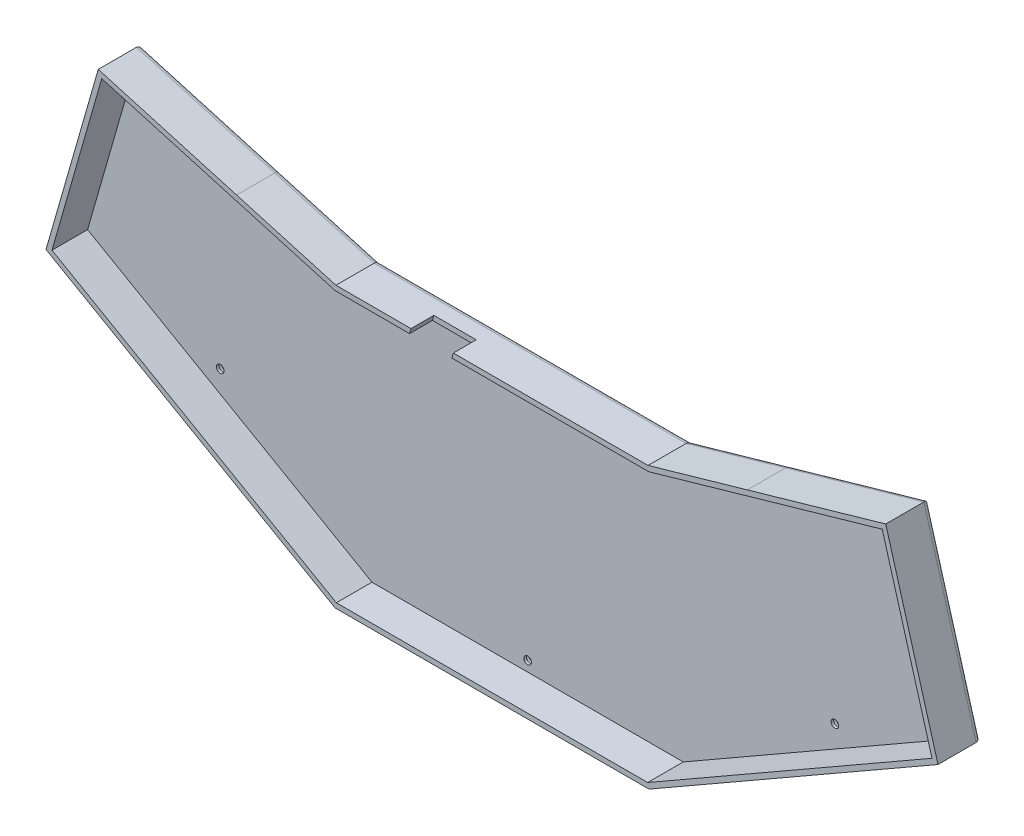
SolidWorks part; units mm, degrees
ref_plane "Plan de face" through (0, 0, 0) normal (0, 0, 1) x (1, 0, 0)
ref_plane "Plan de dessus" through (0, 0, 0) normal (0, 1, 0) x (1, 0, 0)
ref_plane "Plan de droite" through (0, 0, 0) normal (1, 0, 0) x (0, 0, -1)
sketch "Esquisse1" plane through (0, 0, 0) normal (0, 0, 1) x (1, 0, 0)
  line L0 (229.1572, -14.8472) -> (106.4333, -14.8472)
  line L1 (106.4333, -14.8472) -> (67.3725, -3.6491)
  line L2 (67.3725, -3.6491) -> (12.9612, 11.9531)
  line L3 (12.9612, 11.9531) -> (-7.5845, -59.6983)
  line L4 (-7.5845, -59.6983) -> (106.0528, -124.8987)
  line L5 (106.0528, -124.8987) -> (229.5377, -124.8987)
  line L6 (229.5377, -124.8987) -> (343.175, -59.6983)
  line L7 (343.175, -59.6983) -> (322.6293, 11.9531)
  line L8 (322.6293, 11.9531) -> (268.218, -3.6491)
  line L9 (268.218, -3.6491) -> (229.1572, -14.8472)
  line L10 (229.4382, -16.8472) -> (106.1523, -16.8472)
  line L11 (106.1523, -16.8472) -> (66.8213, -5.5716)
  line L12 (66.8213, -5.5716) -> (14.3325, 9.4793)
  line L13 (14.3325, 9.4793) -> (-5.2301, -58.7434)
  line L14 (-5.2301, -58.7434) -> (106.5858, -122.8987)
  line L15 (106.5858, -122.8987) -> (229.0047, -122.8987)
  line L16 (229.0047, -122.8987) -> (340.8206, -58.7434)
  line L17 (340.8206, -58.7434) -> (321.2581, 9.4793)
  line L18 (321.2581, 9.4793) -> (268.7692, -5.5716)
  line L19 (268.7692, -5.5716) -> (229.4382, -16.8472)
  line L20 (322.9036, 12.4479) -> (268.1078, -3.2646) construction
  line L21 (268.1078, -3.2646) -> (229.101, -14.4472) construction
  line L22 (229.101, -14.4472) -> (106.4895, -14.4472) construction
  line L23 (106.4895, -14.4472) -> (67.4828, -3.2646) construction
  line L24 (67.4828, -3.2646) -> (12.687, 12.4479) construction
  line L25 (12.687, 12.4479) -> (-8.0554, -59.8893) construction
  line L26 (-8.0554, -59.8893) -> (105.9462, -125.2987) construction
  line L27 (105.9462, -125.2987) -> (229.6443, -125.2987) construction
  line L28 (229.6443, -125.2987) -> (343.6459, -59.8893) construction
  line L29 (343.6459, -59.8893) -> (322.9036, 12.4479) construction
  line L56 (242.979, -13.5895) -> (243.599, -15.7518) construction
  line L57 (243.599, -15.7518) -> (225.3337, -20.9893) construction
  line L58 (225.3337, -20.9893) -> (226.0229, -23.3926) construction
  line L59 (226.0229, -23.3926) -> (207.7584, -28.6299) construction
  line L60 (207.7584, -28.6299) -> (222.15, -78.8204) construction
  line L61 (222.15, -78.8204) -> (204.6471, -96.9784) construction
  line L62 (204.6471, -96.9784) -> (206.8614, -99.0254) construction
  line L63 (206.8614, -99.0254) -> (229.5776, -121.055) construction
  line L64 (229.5776, -121.055) -> (243.8282, -106.3374) construction
  line L65 (243.8282, -106.3374) -> (278.7547, -90.4535) construction
  line L66 (278.7547, -90.4535) -> (284.9301, -73.6049) construction
  line L67 (284.9301, -73.6049) -> (339.9352, -57.8324) construction
  line L68 (339.9352, -57.8324) -> (322.7757, 2.0099) construction
  line L69 (322.7757, 2.0099) -> (286.2451, -8.465) construction
  line L70 (286.2451, -8.465) -> (284.9358, -3.8987) construction
  line L71 (284.9358, -3.8987) -> (266.6705, -9.1362) construction
  line L72 (266.6705, -9.1362) -> (266.0508, -6.9751) construction
  line L73 (266.0508, -6.9751) -> (242.979, -13.5895) construction
  line L92 (91.9915, -15.7518) -> (92.6116, -13.5895) construction
  line L93 (92.6116, -13.5895) -> (69.5397, -6.9751) construction
  line L94 (69.5397, -6.9751) -> (68.92, -9.1362) construction
  line L95 (68.92, -9.1362) -> (50.6547, -3.8987) construction
  line L96 (50.6547, -3.8987) -> (49.3454, -8.465) construction
  line L97 (49.3454, -8.465) -> (12.8148, 2.0099) construction
  line L98 (12.8148, 2.0099) -> (-4.3447, -57.8324) construction
  line L99 (-4.3447, -57.8324) -> (50.6605, -73.6049) construction
  line L100 (50.6605, -73.6049) -> (56.8358, -90.4535) construction
  line L101 (56.8358, -90.4535) -> (91.7623, -106.3374) construction
  line L102 (91.7623, -106.3374) -> (106.0129, -121.055) construction
  line L103 (106.0129, -121.055) -> (128.7291, -99.0254) construction
  line L104 (128.7291, -99.0254) -> (130.9434, -96.9784) construction
  line L105 (130.9434, -96.9784) -> (113.4405, -78.8204) construction
  line L106 (113.4405, -78.8204) -> (127.8321, -28.6299) construction
  line L107 (127.8321, -28.6299) -> (109.5676, -23.3926) construction
  line L108 (109.5676, -23.3926) -> (110.2568, -20.9893) construction
  line L109 (110.2568, -20.9893) -> (91.9915, -15.7518) construction
  dimension "D1" = 0.4
  dimension "D2" = 2
extrude "Boss.-Extru.1" add sketch "Esquisse1" along normal blind 14
sketch "Esquisse2" plane through (0, 0, 0) normal (0, 0, -1) x (-1, 0, 0)
  line L10 (-229.1572, -14.8472) -> (-268.218, -3.6491)
  line L11 (-268.218, -3.6491) -> (-322.6293, 11.9531)
  line L12 (-322.6293, 11.9531) -> (-343.175, -59.6983)
  line L13 (-343.175, -59.6983) -> (-229.5377, -124.8987)
  line L14 (-229.5377, -124.8987) -> (-106.0528, -124.8987)
  line L15 (-106.0528, -124.8987) -> (7.5845, -59.6983)
  line L16 (7.5845, -59.6983) -> (-12.9612, 11.9531)
  line L17 (-12.9612, 11.9531) -> (-67.3725, -3.6491)
  line L18 (-67.3725, -3.6491) -> (-106.4333, -14.8472)
  line L19 (-106.4333, -14.8472) -> (-229.1572, -14.8472)
  line L20 (-229.1572, -14.8472) -> (-268.218, -3.6491)
  line L21 (-268.218, -3.6491) -> (-322.6293, 11.9531)
  line L22 (-322.6293, 11.9531) -> (-343.175, -59.6983)
  line L23 (-343.175, -59.6983) -> (-229.5377, -124.8987)
  line L24 (-229.5377, -124.8987) -> (-106.0528, -124.8987)
  line L25 (-106.0528, -124.8987) -> (7.5845, -59.6983)
  line L26 (7.5845, -59.6983) -> (-12.9612, 11.9531)
  line L27 (-12.9612, 11.9531) -> (-67.3725, -3.6491)
  line L28 (-67.3725, -3.6491) -> (-106.4333, -14.8472)
  line L29 (-106.4333, -14.8472) -> (-229.1572, -14.8472)
  dimension "D1" = 0
extrude "Boss.-Extru.2" add sketch "Esquisse2" along normal blind 3
fillet "Congé1" radius 2 10 edges at (86.9029, -9.2482, -3) (40.1669, 4.152, -3) (2.6884, -23.8726, -3) (49.2341, -92.2985, -3) (167.7953, -124.8987, -3) (286.3564, -92.2985, -3) (332.9022, -23.8726, -3) (295.4237, 4.152, -3) (248.6876, -9.2482, -3) (167.7953, -14.8472, -3)
sketch "Esquisse3" plane through (0, 0, 0) normal (0, 0, 1) x (1, 0, 0)
  line L31 (164.5068, 7.668) -> (229.6158, 6.136) construction
  line L36 (167.7953, -16.8472) -> (167.7953, -64.7102) construction
  line L37 (229.4382, -16.8472) -> (106.1523, -16.8472) construction
  line L38 (142.2065, 6.9885) -> (157.5867, 2.5784)
  line L39 (142.2065, 6.9885) -> (117.2856, -79.923)
  line L40 (132.6658, -84.3331) -> (117.2856, -79.923)
  line L41 (157.5867, 2.5784) -> (132.6658, -84.3331)
  line L60 (207.7584, -28.6299) -> (222.15, -78.8204) construction
extrude "Enlèv. mat.-Extru.1" cut sketch "Esquisse3" along normal blind 10 from offset 5
sketch "Esquisse7" plane through (0, 0, 0) normal (0, 0, 1) x (1, 0, 0)
  line L0 (321.2581, 9.4793) -> (311.6454, 6.7229) construction
  line L1 (321.2581, 9.4793) -> (268.7692, -5.5716) construction
  line L2 (311.6454, 6.7229) -> (312.748, 2.8779) construction
  line L3 (106.1523, -16.8472) -> (229.4382, -16.8472) construction
  line L4 (167.7953, -16.8472) -> (167.7953, -20.8472) construction
  line L5 (167.7953, -16.8472) -> (167.7953, -122.8987) construction
  line L6 (106.5858, -122.8987) -> (229.0047, -122.8987) construction
  line L7 (167.7953, -69.873) -> (175.0532, -69.873) construction
  line L8 (50.6605, -73.6049) -> (43.2333, -86.5497) construction
  line L10 (50.6605, -73.6049) -> (46.9469, -80.0773) construction
  line L11 (-5.2301, -58.7434) -> (106.5858, -122.8987) construction
  circle A0 centre (312.748, 2.8779) radius 1.5
  circle A1 centre (167.7953, -20.8472) radius 1.5
  circle A2 centre (22.8425, 2.8779) radius 1.5
  circle A3 centre (167.7953, -118.8987) radius 1.5
  circle A4 centre (46.9469, -80.0773) radius 1.5
  circle A5 centre (288.6436, -80.0773) radius 1.5
extrude "Enlèv. mat.-Extru.2" cut sketch "Esquisse7" against normal blind 10
sketch "Esquisse8" plane through (0, 0, -3) normal (0, 0, -1) x (-1, 0, 0)
  circle A5 centre (-288.6436, -80.0773) radius 1.5 construction
  circle A6 centre (-22.8425, 2.8779) radius 3
  circle A7 centre (-46.9469, -80.0773) radius 3
  circle A8 centre (-167.7953, -118.8987) radius 3
  circle A9 centre (-167.7953, -20.8472) radius 3
  circle A10 centre (-288.6436, -80.0773) radius 3
  circle A11 centre (-312.748, 2.8779) radius 3
  circle A12 centre (-46.9469, -80.0773) radius 1.5 construction
extrude "Enlèv. mat.-Extru.3" cut sketch "Esquisse8" against normal blind 2
sketch "Esquisse9" plane through (0, 0, 0) normal (0, 0, 1) x (1, 0, 0)
  line L0 (167.7953, -16.8472) -> (167.7953, -122.8987) construction
  line L1 (229.4382, -16.8472) -> (106.1523, -16.8472) construction
  line L2 (106.5858, -122.8987) -> (229.0047, -122.8987) construction
sketch "Esquisse10" plane through (0, 0, 14) normal (0, 0, 1) x (1, 0, 0)
  line L0 (167.7953, -124.8987) -> (167.7953, -14.8472) construction
  line L1 (106.0528, -124.8987) -> (229.5377, -124.8987) construction
  line L2 (135.9453, -14.8472) -> (106.4333, -14.8472) construction
ref_plane "Plan1" through (167.7953, 0, 0) normal (-1, 0, 0) x (0, 0, 1)
